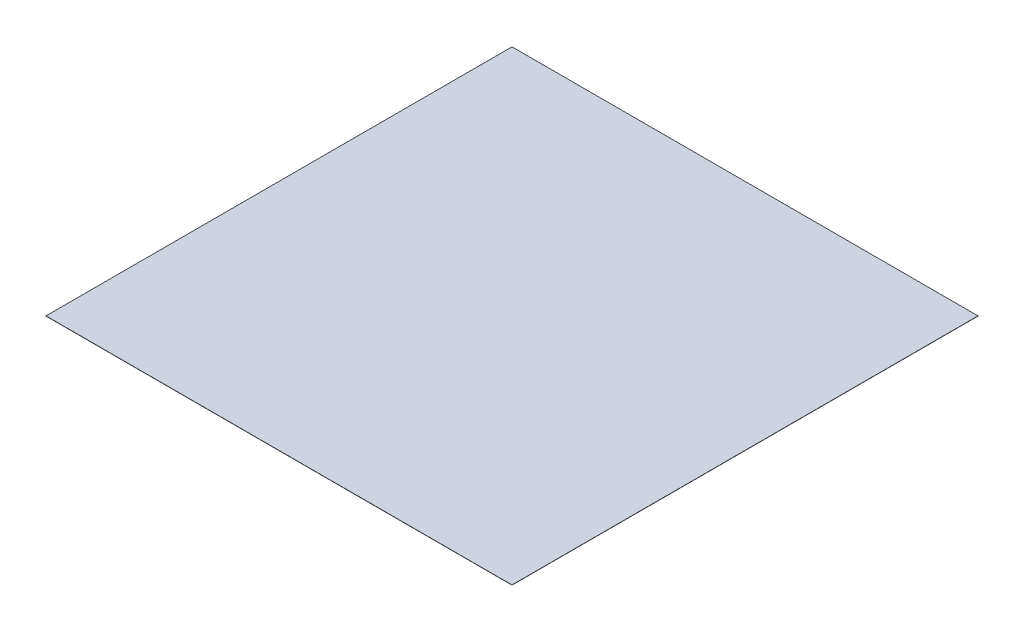
SolidWorks part; units mm, degrees
ref_plane "Front Plane" through (0, 0, 0) normal (0, 0, 1) x (1, 0, 0)
ref_plane "Top Plane" through (0, 0, 0) normal (0, 1, 0) x (1, 0, 0)
ref_plane "Right Plane" through (0, 0, 0) normal (1, 0, 0) x (0, 0, -1)
sketch "Sketch1" plane through (0, 0, 0) normal (0, 1, 0) x (1, 0, 0)
  line L0 (63.638, 56.1771) -> (310.9713, 56.1771) construction
  line L1 (0, 0) -> (210, 0)
  line L2 (0, 0) -> (0, 210)
  line L3 (0, 210) -> (210, 210)
  line L4 (210, 0) -> (210, 210)
  line L5 (104.99, 105.01) -> (105.01, 105.01)
  line L6 (105.01, 104.99) -> (105.01, 105.01)
  line L7 (104.99, 104.99) -> (105.01, 104.99)
  line L8 (104.99, 104.99) -> (104.99, 105.01)
  dimension "D1" = 210
  dimension "D2" = 210
  dimension "D3" = 104.99
extrude "Boss-Extrude1" add sketch "Sketch1" along normal blind 0.1
